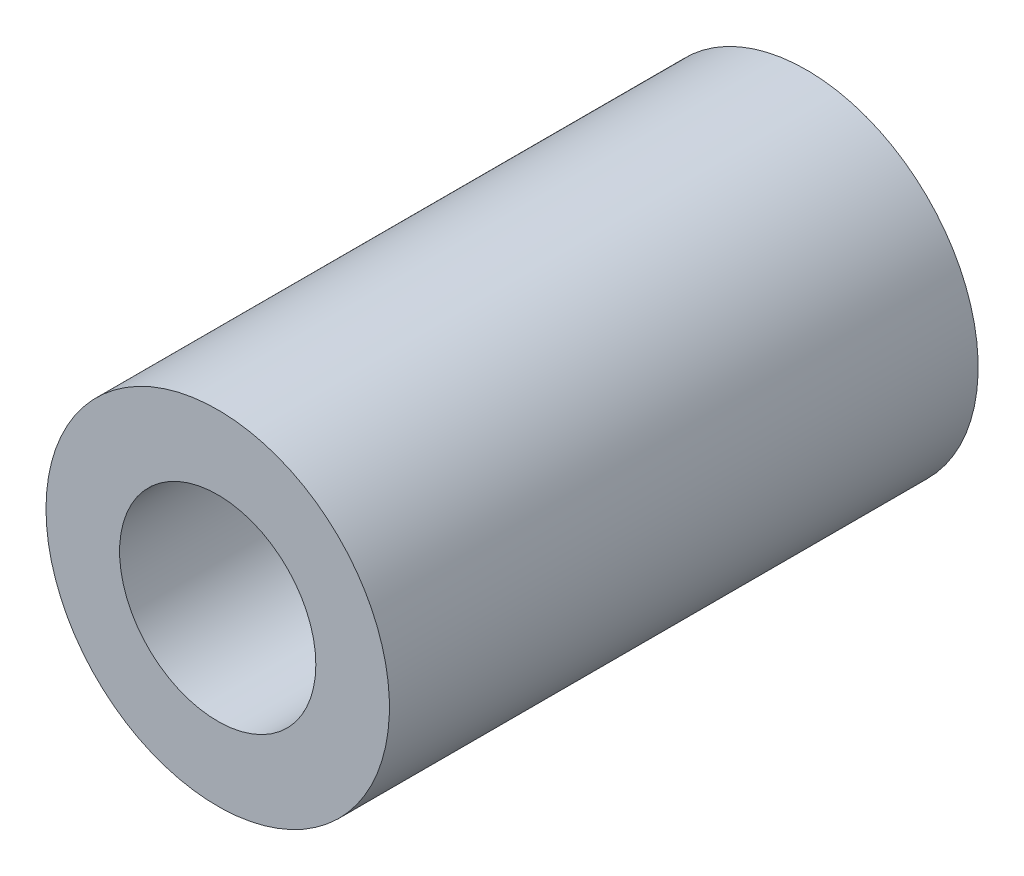
SolidWorks part; units mm, degrees
ref_plane "Front Plane" through (0, 0, 0) normal (0, 0, 1) x (1, 0, 0)
ref_plane "Top Plane" through (0, 0, 0) normal (0, 1, 0) x (1, 0, 0)
ref_plane "Right Plane" through (0, 0, 0) normal (1, 0, 0) x (0, 0, -1)
sketch "Sketch1" plane through (0, 0, 0) normal (0, 0, 1) x (1, 0, 0)
  circle A0 centre (0, 0) radius 11.1125
  dimension "D1" = 22.225
extrude "Boss-Extrude1" add sketch "Sketch1" along normal mid plane 38.1 contours A0
sketch "Sketch10" plane through (0, 0, 19.05) normal (0, 0, 1) x (1, 0, 0)
  circle A0 centre (0, 0) radius 3.2639
hole_wizard "1/2 (0.5) Diameter Hole1" positions "Sketch14" profile "Sketch13" hole size "1/2" standard "ANSI Inch"
sketch "Sketch14" plane through (0, 0, 19.05) normal (0, 0, 1) x (1, 0, 0)
  point P0 (0, 0)
sketch "Sketch13" plane through (0, 0, 19.05) normal (1, 0, 0) x (0, -1, 0)
  line L0 (0, 0) -> (0, 26.1675)
  line L1 (0, 26.1675) -> (6.35, 22.352)
  line L2 (6.35, 22.352) -> (6.35, 0)
  line L5 (6.35, 0) -> (0, 0)
  line L10 (0, 26.1675) -> (-6.35, 22.352) construction
  line L11 (0, -6.35) -> (0, 107.95) construction
  dimension "Hole Dia." = 12.7
  dimension "Hole Depth" = 22.352
  dimension "Drill Angle" = 118
extrude "Cut-Extrude3" cut sketch "Sketch10" against normal through all contours A0
